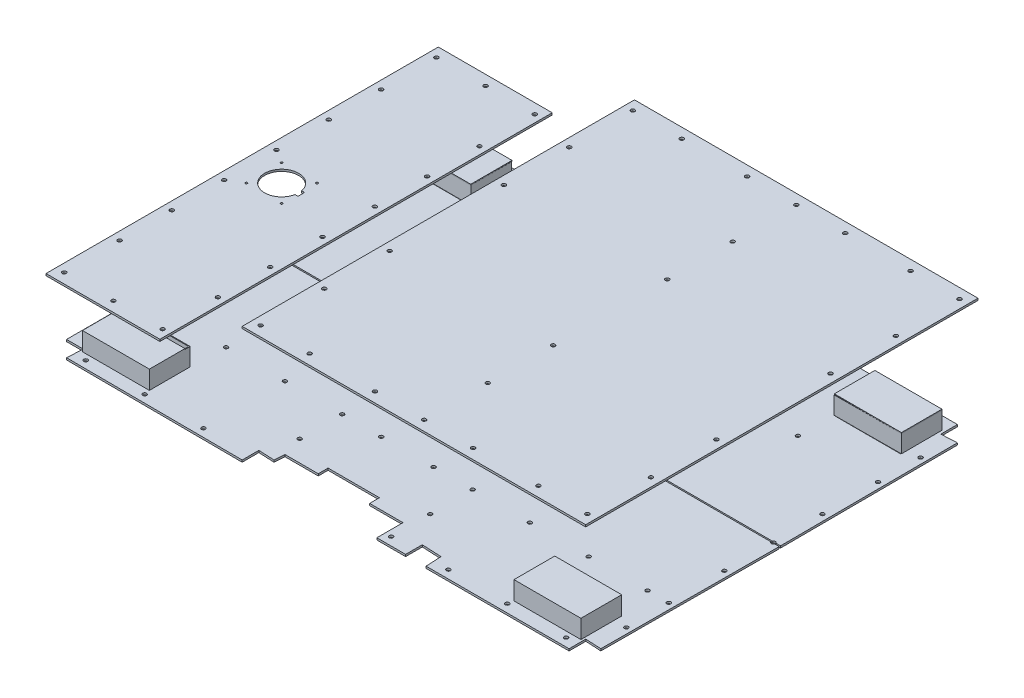
SolidWorks part; units mm, degrees
ref_plane "Front Plane" through (0, 0, 0) normal (0, 0, 1) x (1, 0, 0)
ref_plane "Top Plane" through (0, 0, 0) normal (0, 1, 0) x (1, 0, 0)
ref_plane "Right Plane" through (0, 0, 0) normal (1, 0, 0) x (0, 0, -1)
sketch "Sketch2" plane through (0, 422.0595, 0) normal (0, 1, 0) x (1, 0, 0)
  line L1 (715.0951, -383.2952) -> (690.8951, -384.4952)
  line L2 (690.8951, -384.4952) -> (690.8951, -359.0952)
  line L3 (690.8951, -359.0952) -> (466.2951, -359.0952)
  line L4 (466.2951, -359.0952) -> (465.0951, -383.2952)
  line L5 (465.0951, -383.2952) -> (440.8951, -384.4952)
  line L6 (440.8951, -384.4952) -> (440.8951, -359.0952)
  line L7 (440.8951, -359.0952) -> (390.8951, -359.0952)
  line L8 (390.8951, -359.0952) -> (390.8951, -399.0952)
  line L9 (390.8951, -483.6952) -> (390.8951, -359.0952) construction
  line L10 (390.8951, -399.0952) -> (216.2951, -399.0952)
  line L11 (216.2951, -384.4952) -> (216.2951, -483.6952) construction
  line L12 (216.2951, -399.0952) -> (215.0951, -383.2952)
  line L13 (215.0951, -383.2952) -> (190.8951, -384.4952)
  line L14 (190.8951, -384.4952) -> (190.8951, -359.0952)
  line L15 (190.8951, -359.0952) -> (-84.9049, -360.2952)
  line L16 (-84.9049, -360.2952) -> (-83.7049, -384.4952)
  line L17 (-83.7049, -384.4952) -> (-109.1049, -384.4952)
  line L18 (-109.1049, -384.4952) -> (-109.1049, -933.6952)
  line L19 (-109.1049, -933.6952) -> (-109.1049, -384.4952) construction
  line L20 (715.0951, -383.2952) -> (716.2951, -659.0952)
  line L21 (716.2951, -384.4952) -> (716.2951, -933.6952) construction
  line L22 (716.2951, -659.0952) -> (-109.1049, -659.0952) construction
  line L23 (715.0951, -934.8952) -> (716.2951, -659.0952)
  line L24 (-83.7049, -933.6952) -> (-109.1049, -933.6952)
  line L25 (-84.9049, -957.8952) -> (-83.7049, -933.6952)
  line L26 (190.8951, -959.0952) -> (-84.9049, -957.8952)
  line L27 (190.8951, -933.6952) -> (190.8951, -959.0952)
  line L28 (215.0951, -934.8952) -> (190.8951, -933.6952)
  line L29 (216.2951, -919.0952) -> (215.0951, -934.8952)
  line L30 (390.8951, -919.0952) -> (216.2951, -919.0952)
  line L31 (390.8951, -959.0952) -> (390.8951, -919.0952)
  line L32 (440.8951, -959.0952) -> (390.8951, -959.0952)
  line L33 (440.8951, -933.6952) -> (440.8951, -959.0952)
  line L34 (465.0951, -934.8952) -> (440.8951, -933.6952)
  line L35 (466.2951, -959.0952) -> (465.0951, -934.8952)
  line L36 (690.8951, -959.0952) -> (466.2951, -959.0952)
  line L37 (690.8951, -933.6952) -> (690.8951, -959.0952)
  line L38 (715.0951, -934.8952) -> (690.8951, -933.6952)
  line L39 (712.1088, -386.4469) -> (713.2907, -658.0952)
  line L40 (712.1088, -386.4469) -> (687.8951, -387.6476)
  line L41 (687.8951, -387.6476) -> (687.8951, -362.0952)
  line L42 (687.8951, -362.0952) -> (469.15, -362.0952)
  line L43 (469.15, -362.0952) -> (467.9569, -386.1569)
  line L44 (467.9569, -386.1569) -> (437.8951, -387.6476)
  line L45 (437.8951, -387.6476) -> (437.8951, -362.0952)
  line L46 (437.8951, -362.0952) -> (393.8951, -362.0952)
  line L47 (393.8951, -362.0952) -> (393.8951, -402.0952)
  line L48 (393.8951, -402.0952) -> (213.5143, -402.0952)
  line L49 (213.5143, -402.0952) -> (212.325, -386.4362)
  line L50 (212.325, -386.4362) -> (187.8951, -387.6476)
  line L51 (187.8951, -387.6476) -> (187.8951, -362.1082)
  line L52 (187.8951, -362.1082) -> (-81.7531, -363.2815)
  line L53 (-81.7531, -363.2815) -> (-80.5525, -387.4952)
  line L54 (-80.5525, -387.4952) -> (-106.1049, -387.4952)
  line L55 (-106.1049, -387.4952) -> (-106.1049, -658.0952)
  line L56 (-80.5525, -930.6952) -> (-106.1049, -930.6952)
  line L57 (-81.7531, -954.9089) -> (-80.5525, -930.6952)
  line L58 (187.8951, -956.0821) -> (-81.7531, -954.9089)
  line L59 (187.8951, -930.5427) -> (187.8951, -956.0821)
  line L60 (212.325, -931.7541) -> (187.8951, -930.5427)
  line L61 (213.5143, -916.0952) -> (212.325, -931.7541)
  line L62 (393.8951, -916.0952) -> (213.5143, -916.0952)
  line L63 (393.8951, -956.0952) -> (393.8951, -916.0952)
  line L64 (437.8951, -956.0952) -> (393.8951, -956.0952)
  line L65 (437.8951, -930.5427) -> (437.8951, -956.0952)
  line L66 (467.9569, -932.0334) -> (437.8951, -930.5427)
  line L67 (469.15, -956.0952) -> (467.9569, -932.0334)
  line L68 (687.8951, -956.0952) -> (469.15, -956.0952)
  line L69 (687.8951, -930.5427) -> (687.8951, -956.0952)
  line L70 (712.1088, -931.7434) -> (687.8951, -930.5427)
  line L71 (712.1088, -931.7434) -> (713.2907, -660.0952)
  line L72 (716.2951, -658.0952) -> (716.2907, -658.0952)
  line L73 (716.2951, -660.0952) -> (716.2907, -660.0952)
  line L74 (713.2907, -660.0952) -> (-106.1049, -660.0952)
  line L75 (713.2907, -658.0952) -> (-106.1049, -658.0952)
  line L76 (716.2951, -660.0952) -> (-109.1049, -660.0952) construction
  line L77 (-106.1049, -660.0952) -> (-106.1049, -930.6952)
  line L78 (716.2951, -658.0952) -> (-109.1049, -658.0952) construction
  line L80 (-106.1049, -387.4952) -> (-106.1049, -930.6952) construction
  line L81 (712.1088, -386.4469) -> (713.2951, -659.0952) construction
  line L82 (712.1088, -931.7434) -> (713.2951, -659.0952) construction
  circle A0 centre (-96.2049, -884.0952) radius 3 construction
  circle A1 centre (116.2951, -819.0952) radius 3 construction
  circle A2 centre (-63.7049, -819.0952) radius 3 construction
  circle A3 centre (-96.2049, -819.0952) radius 3 construction
  circle A4 centre (-96.2049, -884.0952) radius 3
  circle A5 centre (116.2951, -819.0952) radius 3
  circle A6 centre (-63.7049, -819.0952) radius 3
  circle A7 centre (-96.2049, -819.0952) radius 3
  circle A8 centre (-96.2049, -734.0952) radius 3 construction
  circle A9 centre (-96.2049, -734.0952) radius 3
  circle A10 centre (116.2951, -943.6952) radius 3 construction
  circle A11 centre (26.2951, -943.6952) radius 3 construction
  circle A12 centre (-63.7049, -943.6952) radius 3 construction
  circle A13 centre (116.2951, -943.6952) radius 3
  circle A14 centre (26.2951, -943.6952) radius 3
  circle A15 centre (-63.7049, -943.6952) radius 3
  circle A16 centre (-96.2049, -659.0952) radius 3 construction
  circle A17 centre (-96.2049, -659.0952) radius 3
  circle A18 centre (26.2951, -819.0952) radius 3 construction
  circle A19 centre (26.2951, -819.0952) radius 3
  circle A20 centre (343.5951, -819.0952) radius 3 construction
  circle A21 centre (203.7951, -734.0952) radius 3 construction
  circle A22 centre (263.5951, -819.0952) radius 3 construction
  circle A23 centre (203.7951, -819.0952) radius 3 construction
  circle A24 centre (203.7951, -884.0952) radius 3 construction
  circle A25 centre (343.5951, -819.0952) radius 3
  circle A26 centre (203.7951, -734.0952) radius 3
  circle A27 centre (263.5951, -819.0952) radius 3
  circle A28 centre (203.7951, -819.0952) radius 3
  circle A29 centre (203.7951, -884.0952) radius 3
  circle A30 centre (203.7951, -659.0952) radius 3 construction
  circle A31 centre (203.7951, -659.0952) radius 3
  circle A32 centre (26.2951, -499.0952) radius 3 construction
  circle A33 centre (26.2951, -499.0952) radius 3
  circle A34 centre (116.2951, -499.0952) radius 3 construction
  circle A35 centre (116.2951, -499.0952) radius 3
  circle A36 centre (203.7951, -499.0952) radius 3 construction
  circle A37 centre (203.7951, -499.0952) radius 3
  circle A38 centre (203.7951, -434.0952) radius 3 construction
  circle A39 centre (203.7951, -434.0952) radius 3
  circle A40 centre (116.2951, -374.4952) radius 3 construction
  circle A41 centre (116.2951, -374.4952) radius 3
  circle A42 centre (26.2951, -374.4952) radius 3 construction
  circle A43 centre (26.2951, -374.4952) radius 3
  circle A44 centre (-63.7049, -374.4952) radius 3 construction
  circle A45 centre (-63.7049, -374.4952) radius 3
  circle A46 centre (-96.2049, -434.0952) radius 3 construction
  circle A47 centre (-96.2049, -499.0952) radius 3 construction
  circle A48 centre (-96.2049, -584.0952) radius 3 construction
  circle A49 centre (-96.2049, -434.0952) radius 3
  circle A50 centre (-96.2049, -499.0952) radius 3
  circle A51 centre (-96.2049, -584.0952) radius 3
  circle A52 centre (-63.7049, -499.0952) radius 3 construction
  circle A53 centre (-63.7049, -499.0952) radius 3
  circle A54 centre (203.7951, -584.0952) radius 3 construction
  circle A55 centre (203.7951, -584.0952) radius 3
  circle A56 centre (403.3951, -584.0952) radius 3 construction
  circle A57 centre (403.3951, -584.0952) radius 3
  circle A58 centre (490.8951, -499.0952) radius 3 construction
  circle A59 centre (490.8951, -499.0952) radius 3
  circle A60 centre (580.8951, -499.0952) radius 3 construction
  circle A61 centre (580.8951, -499.0952) radius 3
  circle A62 centre (490.8951, -374.4952) radius 3 construction
  circle A63 centre (490.8951, -374.4952) radius 3
  circle A64 centre (580.8951, -374.4952) radius 3 construction
  circle A65 centre (580.8951, -374.4952) radius 3
  circle A66 centre (703.3951, -584.0952) radius 3 construction
  circle A67 centre (703.3951, -499.0952) radius 3 construction
  circle A68 centre (703.3951, -434.0952) radius 3 construction
  circle A69 centre (670.8951, -374.4952) radius 3 construction
  circle A70 centre (703.3951, -584.0952) radius 3
  circle A71 centre (703.3951, -499.0952) radius 3
  circle A72 centre (703.3951, -434.0952) radius 3
  circle A73 centre (670.8951, -374.4952) radius 3
  circle A74 centre (703.3951, -884.0952) radius 3 construction
  circle A75 centre (703.3951, -819.0952) radius 3 construction
  circle A76 centre (703.3951, -734.0952) radius 3 construction
  circle A77 centre (703.3951, -659.0952) radius 3 construction
  circle A78 centre (703.3951, -884.0952) radius 3
  circle A79 centre (703.3951, -819.0952) radius 3
  circle A80 centre (703.3951, -734.0952) radius 3
  circle A81 centre (703.3951, -659.0952) radius 3
  circle A82 centre (490.8951, -943.6952) radius 3 construction
  circle A83 centre (580.8951, -943.6952) radius 3 construction
  circle A84 centre (670.8951, -943.6952) radius 3 construction
  circle A85 centre (490.8951, -943.6952) radius 3
  circle A86 centre (580.8951, -943.6952) radius 3
  circle A87 centre (670.8951, -943.6952) radius 3
  circle A89 centre (580.8951, -819.0952) radius 3 construction
  circle A90 centre (670.8951, -819.0952) radius 3 construction
  circle A91 centre (580.8951, -819.0952) radius 3
  circle A92 centre (670.8951, -819.0952) radius 3
  circle A93 centre (490.8951, -819.0952) radius 3 construction
  circle A94 centre (490.8951, -819.0952) radius 3
  circle A95 centre (403.3951, -943.6952) radius 3 construction
  circle A96 centre (403.3951, -884.0952) radius 3 construction
  circle A97 centre (403.3951, -819.0952) radius 3 construction
  circle A98 centre (403.3951, -734.0952) radius 3 construction
  circle A99 centre (403.3951, -943.6952) radius 3
  circle A100 centre (403.3951, -884.0952) radius 3
  circle A101 centre (403.3951, -819.0952) radius 3
  circle A102 centre (403.3951, -734.0952) radius 3
  circle A103 centre (403.3951, -659.0952) radius 3 construction
  circle A104 centre (403.3951, -499.0952) radius 3 construction
  circle A105 centre (403.3951, -434.0952) radius 3 construction
  circle A106 centre (403.3951, -374.4952) radius 3 construction
  circle A107 centre (403.3951, -659.0952) radius 3
  circle A108 centre (403.3951, -499.0952) radius 3
  circle A109 centre (403.3951, -434.0952) radius 3
  circle A110 centre (403.3951, -374.4952) radius 3
  circle A111 centre (343.5951, -499.0952) radius 3 construction
  circle A113 centre (263.5951, -499.0952) radius 3 construction
  circle A114 centre (343.5951, -499.0952) radius 3
  circle A115 centre (263.5951, -499.0952) radius 3
  dimension "D1" = 40
  dimension "D2" = 3
  dimension "D3" = 1
  dimension "D4" = 1
extrude "Boss-Extrude1" add sketch "Sketch2" along normal blind 3 contours A107 L75 A81 L39 L40 L41 L42 L43 L44 L45 L46 L47 L48 L49 L50 L51 L52 L53 L54 L55 A17 A31 A115 A114 A110 A109 A108 A73 A72 A71 A70 A65 A63 A61 | A107 L74 A31 A17 L77 L56 L57 L58 L59 L60 L61 L62 L63 L64 L65 L66 L67 L68 L69 L70 L71 A81 A102 A101 A100 A99 A94 A92 A91 A87 A86 A85 A80 A79 | A43 | A45
sketch "Sketch4" plane through (0, 602.0595, 0) normal (0, 1, 0) x (1, 0, 0)
  line L0 (716.2951, -359.0952) -> (190.8951, -359.0952) construction
  line L1 (190.8951, -359.0952) -> (190.8951, -959.0952) construction
  line L2 (190.8951, -933.6952) -> (190.8951, -384.4952) construction
  line L3 (716.2951, -959.0952) -> (716.2951, -359.0952) construction
  line L4 (190.8951, -959.0952) -> (716.2951, -959.0952) construction
  line L5 (716.2951, -359.0952) -> (190.8951, -359.0952)
  line L6 (190.8951, -359.0952) -> (190.8951, -959.0952)
  line L7 (190.8951, -933.6952) -> (190.8951, -384.4952)
  line L8 (716.2951, -959.0952) -> (716.2951, -359.0952)
  line L9 (190.8951, -959.0952) -> (716.2951, -959.0952)
  line L10 (190.8951, -359.0952) -> (716.2951, -959.0952) construction
  line L11 (190.8951, -959.0952) -> (716.2951, -359.0952) construction
  line L12 (453.5951, -659.0952) -> (716.2951, -659.0952) construction
  circle A1 centre (628.5951, -943.6952) radius 3 construction
  circle A2 centre (703.3951, -943.6952) radius 3 construction
  circle A3 centre (528.5951, -943.6952) radius 3 construction
  circle A4 centre (703.3951, -846.3952) radius 3 construction
  circle A5 centre (703.3951, -746.3952) radius 3 construction
  circle A6 centre (453.7951, -943.6952) radius 3 construction
  circle A7 centre (453.7951, -846.3952) radius 3 construction
  circle A8 centre (378.5951, -943.6952) radius 3 construction
  circle A9 centre (278.5951, -943.6952) radius 3 construction
  circle A10 centre (203.7951, -943.6952) radius 3 construction
  circle A11 centre (203.7951, -746.3952) radius 3 construction
  circle A12 centre (203.7951, -846.3952) radius 3 construction
  circle A13 centre (453.7951, -746.3952) radius 3 construction
  circle A14 centre (453.7951, -746.3952) radius 3
  circle A15 centre (203.7951, -846.3952) radius 3
  circle A16 centre (203.7951, -746.3952) radius 3
  circle A17 centre (203.7951, -943.6952) radius 3
  circle A18 centre (278.5951, -943.6952) radius 3
  circle A19 centre (378.5951, -943.6952) radius 3
  circle A20 centre (453.7951, -846.3952) radius 3
  circle A21 centre (453.7951, -943.6952) radius 3
  circle A22 centre (703.3951, -746.3952) radius 3
  circle A23 centre (703.3951, -846.3952) radius 3
  circle A24 centre (528.5951, -943.6952) radius 3
  circle A25 centre (703.3951, -943.6952) radius 3
  circle A26 centre (628.5951, -943.6952) radius 3
  circle A40 centre (628.5951, -374.4952) radius 3
  circle A41 centre (703.3951, -374.4952) radius 3
  circle A42 centre (528.5951, -374.4952) radius 3
  circle A43 centre (703.3951, -471.7952) radius 3
  circle A44 centre (703.3951, -571.7952) radius 3
  circle A45 centre (453.7951, -374.4952) radius 3
  circle A46 centre (453.7951, -471.7952) radius 3
  circle A47 centre (378.5951, -374.4952) radius 3
  circle A48 centre (278.5951, -374.4952) radius 3
  circle A49 centre (203.7951, -374.4952) radius 3
  circle A50 centre (203.7951, -571.7952) radius 3
  circle A51 centre (203.7951, -471.7952) radius 3
  circle A52 centre (453.7951, -571.7952) radius 3
extrude "Boss-Extrude2" add sketch "Sketch4" along normal blind 3 separate body contours L5 L6 L9 L8 | A49 | A48 | A47 | A46 | A51 | A50 | A52 | A45 | A42 | A40 | A41 | A43 | A44 | A22 | A14 | A16 | A15 | A18 | A19 | A20 | A21 | A24 | A26 | A23 | A25 | A17
sketch "Sketch6" plane through (0, 522.0595, 0) normal (0, 1, 0) x (1, 0, 0)
  line L0 (-109.1049, -959.0952) -> (-109.1049, -359.0952) construction
  line L1 (65.0951, -384.4952) -> (65.0951, -933.6952) construction
  line L2 (-109.1049, -959.0952) -> (-109.1049, -359.0952)
  line L3 (65.0951, -384.4952) -> (65.0951, -933.6952)
  line L4 (65.0951, -933.6952) -> (65.0951, -959.0952)
  line L5 (190.8951, -959.0952) -> (-109.1049, -959.0952) construction
  line L6 (65.0951, -959.0952) -> (-109.1049, -959.0952)
  line L7 (65.0951, -384.4952) -> (65.0951, -359.0952)
  line L8 (190.8951, -359.0952) -> (-109.1049, -359.0952) construction
  line L9 (65.0951, -359.0952) -> (-109.1049, -359.0952)
  line L10 (65.0951, -659.0952) -> (-109.1049, -659.0952) construction
  circle A0 centre (-96.6049, -943.6952) radius 3 construction
  circle A1 centre (-21.3999, -943.6952) radius 3 construction
  circle A2 centre (53.7951, -943.6952) radius 3 construction
  circle A3 centre (-96.6049, -943.6952) radius 3
  circle A4 centre (-21.3999, -943.6952) radius 3
  circle A5 centre (53.7951, -943.6952) radius 3
  circle A6 centre (-96.6049, -859.0952) radius 3 construction
  circle A7 centre (53.7951, -859.0952) radius 3 construction
  circle A8 centre (-96.6049, -859.0952) radius 3
  circle A9 centre (53.7951, -859.0952) radius 3
  circle A10 centre (53.7951, -699.0952) radius 3 construction
  circle A11 centre (-96.6049, -699.0952) radius 3 construction
  circle A12 centre (53.7951, -779.0952) radius 3 construction
  circle A13 centre (-96.6049, -779.0952) radius 3 construction
  circle A14 centre (53.7951, -699.0952) radius 3
  circle A15 centre (-96.6049, -699.0952) radius 3
  circle A16 centre (53.7951, -779.0952) radius 3
  circle A17 centre (-96.6049, -779.0952) radius 3
  circle A27 centre (-96.6049, -619.0952) radius 3
  circle A28 centre (-96.6049, -539.0952) radius 3
  circle A29 centre (53.7951, -539.0952) radius 3
  circle A30 centre (53.7951, -619.0952) radius 3
  circle A31 centre (53.7951, -459.0952) radius 3
  circle A32 centre (-96.6049, -459.0952) radius 3
  circle A33 centre (53.7951, -374.4952) radius 3
  circle A34 centre (-21.3999, -374.4952) radius 3
  circle A35 centre (-96.6049, -374.4952) radius 3
extrude "Boss-Extrude3" add sketch "Sketch6" along normal blind 3 separate body
sketch "Sketch9" plane through (0, 525.0595, 0) normal (0, 1, 0) x (1, 0, 0)
  line L0 (-48.7049, -659.0952) -> (-22.7049, -659.0952) construction
  line L1 (-48.7049, -654.0952) -> (-22.7049, -654.0952) construction
  line L2 (-48.7049, -664.0952) -> (-22.7049, -664.0952) construction
  line L3 (-23.1902, -654.0952) -> (-18.6902, -654.0952)
  line L4 (-18.6902, -654.0952) -> (-18.6902, -664.0952)
  line L5 (-18.6902, -664.0952) -> (-23.1902, -664.0952)
  arc A0 (-23.1902, -654.0952) -> (-23.1902, -664.0952) centre (-48.7049, -659.0952) ccw
  dimension "D1" = 52
  dimension "D4" = 4.5
  dimension "D2" = 5
  dimension "D3" = 5
extrude "Cut-Extrude1" cut sketch "Sketch9" against normal up to next (3 mm away)
sketch "Sketch10" plane through (0, 525.0595, 0) normal (0, 1, 0) x (1, 0, 0)
  circle A0 centre (-21.7049, -632.0952) radius 1.6
  circle A1 centre (-21.7049, -686.0952) radius 1.6
  circle A2 centre (-75.7049, -632.0952) radius 1.6
  circle A3 centre (-75.7049, -686.0952) radius 1.6
  dimension "D1" = 3.2
  dimension "D2" = 3.2
  dimension "D3" = 3.2
  dimension "D4" = 3.2
extrude "Cut-Extrude4" cut sketch "Sketch10" against normal up to next (3 mm away)
sketch "Sketch11" plane through (0, 422.0595, 0) normal (0, -1, 0) x (1, 0, 0)
  line L0 (264.2951, 916.0952) -> (264.2951, 901.0952)
  line L1 (393.8951, 916.0952) -> (213.5143, 916.0952) construction
  line L2 (264.2951, 901.0952) -> (342.8951, 901.0952)
  line L3 (342.8951, 901.0952) -> (342.8951, 916.0952)
  line L4 (264.2951, 402.0952) -> (342.8951, 402.0952)
  line L5 (390.8951, 959.0952) -> (390.8951, 834.4952) construction
  line L6 (216.2951, 959.0952) -> (216.2951, 834.4952) construction
  line L7 (216.2951, 659.0952) -> (416.2951, 659.0952) construction
  line L8 (216.2951, 809.0952) -> (216.2951, 509.0952) construction
  line L9 (416.2951, 809.0952) -> (416.2951, 509.0952) construction
  line L10 (342.8951, 417.0952) -> (342.8951, 402.0952)
  line L11 (264.2951, 417.0952) -> (342.8951, 417.0952)
  line L12 (264.2951, 402.0952) -> (264.2951, 417.0952)
  line L13 (264.2951, 916.0952) -> (342.8951, 916.0952)
  dimension "D1" = 15
  dimension "D2" = 48
  dimension "D3" = 48
extrude "Cut-Extrude5" cut sketch "Sketch11" against normal up to next (3 mm away)
sketch "Sketch13" plane through (0, 422.0595, 0) normal (0, -1, 0) x (1, 0, 0)
  line L1 (683.5951, 933.6952) -> (583.5951, 933.6952)
  line L3 (683.5951, 873.6952) -> (583.5951, 873.6952)
  line L4 (583.5951, 933.6952) -> (583.5951, 873.6952)
  line L7 (303.5951, 901.0952) -> (303.5951, 417.0952) construction
  line L22 (683.5951, 933.6952) -> (683.5951, 873.6952)
  line L24 (264.2951, 901.0952) -> (342.8951, 901.0952) construction
  line L25 (342.8951, 417.0952) -> (264.2951, 417.0952) construction
  line L26 (303.5951, 659.0952) -> (712.9729, 659.0952) construction
  line L29 (687.8951, 956.0952) -> (469.15, 956.0952) construction
  line L30 (683.5951, 384.4952) -> (683.5951, 444.4952)
  line L31 (583.5951, 384.4952) -> (583.5951, 444.4952)
  line L32 (683.5951, 444.4952) -> (583.5951, 444.4952)
  line L33 (683.5951, 384.4952) -> (583.5951, 384.4952)
  line L34 (-76.4049, 933.6952) -> (-76.4049, 873.6952)
  line L35 (23.5951, 933.6952) -> (23.5951, 873.6952)
  line L36 (-76.4049, 873.6952) -> (23.5951, 873.6952)
  line L37 (-76.4049, 933.6952) -> (23.5951, 933.6952)
  line L38 (-76.4049, 384.4952) -> (23.5951, 384.4952)
  line L39 (-76.4049, 444.4952) -> (23.5951, 444.4952)
  line L40 (23.5951, 384.4952) -> (23.5951, 444.4952)
  line L41 (-76.4049, 384.4952) -> (-76.4049, 444.4952)
  dimension "D1" = 60
  dimension "D2" = 100
  dimension "D3" = 22.4
  dimension "D4" = 380
extrude "Cut-Extrude6" cut sketch "Sketch13" against normal up to next (3 mm away)
sketch "Sketch15" plane through (0, 422.0595, 0) normal (0, -1, 0) x (1, 0, 0)
  line L0 (583.5951, 933.6952) -> (583.5951, 873.6952) construction
  line L1 (583.5951, 873.6952) -> (683.5951, 873.6952) construction
  line L2 (683.5951, 933.6952) -> (583.5951, 933.6952) construction
  line L3 (683.5951, 873.6952) -> (683.5951, 933.6952) construction
  line L4 (583.5951, 933.6952) -> (583.5951, 873.6952)
  line L5 (583.5951, 873.6952) -> (683.5951, 873.6952)
  line L6 (683.5951, 933.6952) -> (583.5951, 933.6952)
  line L7 (683.5951, 873.6952) -> (683.5951, 933.6952)
  line L8 (582.3951, 934.8952) -> (582.3951, 872.4952)
  line L9 (582.3951, 872.4952) -> (684.7951, 872.4952)
  line L10 (684.7951, 872.4952) -> (684.7951, 934.8952)
  line L11 (684.7951, 934.8952) -> (582.3951, 934.8952)
  line L13 (303.5951, 901.0952) -> (303.5951, 416.7343) construction
  line L14 (264.2951, 901.0952) -> (342.8951, 901.0952) construction
  line L15 (303.5951, 658.9147) -> (713.2907, 658.0952) construction
  line L16 (683.6879, 381.4114) -> (581.2887, 381.8211)
  line L17 (683.9375, 443.8109) -> (683.6879, 381.4114)
  line L18 (581.5384, 444.2206) -> (683.9375, 443.8109)
  line L19 (581.2887, 381.8211) -> (581.5384, 444.2206)
  line L20 (682.7327, 442.6157) -> (682.4927, 382.6162)
  line L21 (682.4927, 382.6162) -> (582.4935, 383.0163)
  line L22 (582.7335, 443.0158) -> (682.7327, 442.6157)
  line L23 (582.4935, 383.0163) -> (582.7335, 443.0158)
  line L24 (24.6967, 383.0163) -> (24.4566, 443.0158)
  line L25 (24.4566, 443.0158) -> (-75.5426, 442.6157)
  line L26 (-75.3025, 382.6162) -> (24.6967, 383.0163)
  line L27 (-75.5426, 442.6157) -> (-75.3025, 382.6162)
  line L28 (25.9015, 381.8211) -> (25.6518, 444.2206)
  line L29 (25.6518, 444.2206) -> (-76.7474, 443.8109)
  line L30 (-76.7474, 443.8109) -> (-76.4977, 381.4114)
  line L31 (-76.4977, 381.4114) -> (25.9015, 381.8211)
  line L32 (-77.6049, 934.8952) -> (24.7951, 934.8952)
  line L33 (-77.6049, 872.4952) -> (-77.6049, 934.8952)
  line L34 (24.7951, 872.4952) -> (-77.6049, 872.4952)
  line L35 (24.7951, 934.8952) -> (24.7951, 872.4952)
  line L36 (-76.4049, 873.6952) -> (-76.4049, 933.6952)
  line L37 (-76.4049, 933.6952) -> (23.5951, 933.6952)
  line L38 (23.5951, 873.6952) -> (-76.4049, 873.6952)
  line L39 (23.5951, 933.6952) -> (23.5951, 873.6952)
  dimension "D1" = 1.2
extrude "Boss-Extrude4" add sketch "Sketch15" against normal blind 27 from surface at -3 starting at face at (633.5951, 425.0595, 414.4952)
sketch "Sketch16" plane through (0, 452.0595, 0) normal (0, 1, 0) x (-1, 0, 0)
  line L0 (-684.7951, 934.8952) -> (-582.3951, 934.8952) construction
  line L1 (-684.7951, 934.8952) -> (-582.3951, 934.8952)
  line L2 (-684.7951, 934.8952) -> (-684.7951, 872.4952)
  line L3 (-684.7951, 872.4952) -> (-582.3951, 872.4952)
  line L4 (-582.3951, 934.8952) -> (-582.3951, 872.4952)
  line L5 (-684.7951, 872.4952) -> (-684.7951, 934.8952) construction
  line L6 (-582.3951, 934.8952) -> (-582.3951, 872.4952) construction
  line L7 (-582.3951, 872.4952) -> (-684.7951, 872.4952) construction
  line L8 (-581.5384, 444.2206) -> (-581.2887, 381.8211) construction
  line L9 (-683.9375, 443.8109) -> (-581.2887, 443.8109)
  line L10 (-683.9375, 443.8109) -> (-683.9375, 381.8211)
  line L11 (-683.9375, 381.8211) -> (-581.2887, 381.8211)
  line L12 (-581.2887, 443.8109) -> (-581.2887, 381.8211)
  line L13 (-581.2887, 381.8211) -> (-683.6879, 381.4114) construction
  line L14 (77.6049, 934.8952) -> (77.6049, 872.4952) construction
  line L15 (-24.7951, 934.8952) -> (77.6049, 934.8952)
  line L16 (-24.7951, 934.8952) -> (-24.7951, 880.4952)
  line L17 (-24.7951, 880.4952) -> (77.6049, 880.4952)
  line L18 (77.6049, 934.8952) -> (77.6049, 880.4952)
  line L19 (76.7474, 443.8109) -> (76.4977, 381.4114) construction
  line L20 (-25.6518, 444.2206) -> (76.4964, 444.2206)
  line L21 (-25.6518, 444.2206) -> (-25.6518, 381.0889)
  line L22 (-25.6518, 381.0889) -> (76.4964, 381.0889)
  line L23 (76.4964, 444.2206) -> (76.4964, 381.0889)
extrude "Boss-Extrude5" add sketch "Sketch16" along normal blind 1.2
